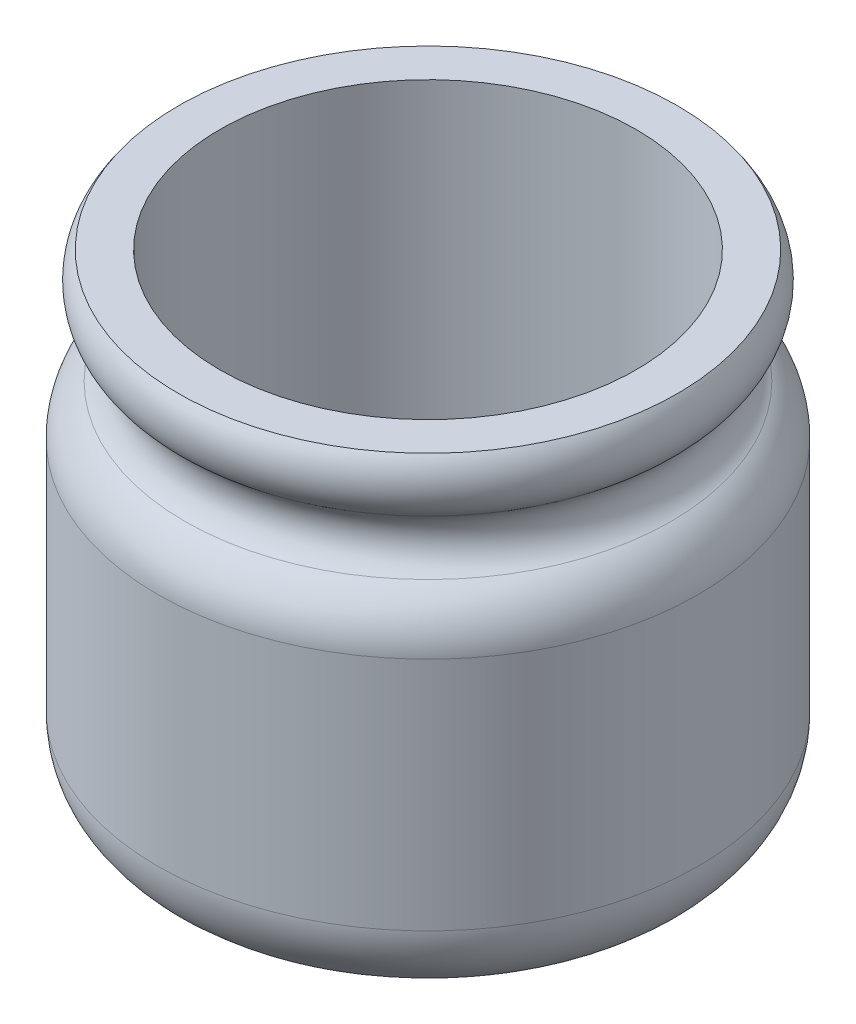
SolidWorks part; units mm, degrees
ref_plane "정면" through (0, 0, 0) normal (0, 0, 1) x (1, 0, 0)
ref_plane "윗면" through (0, 0, 0) normal (0, 1, 0) x (1, 0, 0)
ref_plane "우측면" through (0, 0, 0) normal (1, 0, 0) x (0, 0, -1)
sketch "스케치2" plane through (0, 0, 0) normal (1, 0, 0) x (0, 0, -1)
  line L0 (10.1, 0) -> (12.1, 0)
  line L1 (13.1, -7.9444) -> (13.1, -19.3593)
  line L2 (9.2593, -23.2) -> (0, -23.2)
  line L3 (0, -20.2) -> (0, 0) construction
  line L4 (10.1, 0) -> (10.1, -20.2)
  line L5 (10.1, -20.2) -> (0, -20.2)
  line L6 (0, -20.2) -> (0, -23.2)
  arc A0 (12.1, 0) -> (11.7965, -2.8572) centre (10.4532, -1.2698) cw
  arc A1 (11.7965, -2.8572) -> (11.7965, -5.5189) centre (12.6772, -4.1881) ccw
  arc A2 (11.7965, -5.5189) -> (13.1, -7.9444) centre (10.1915, -7.9444) cw
  arc A3 (13.1, -19.3593) -> (9.2593, -23.2) centre (9.2593, -19.3593) cw
  dimension "D3" = 20.2
  dimension "D4" = 2
  dimension "D1" = 10.1
  dimension "D2" = 3
  dimension "D5" = 3
  dimension "D8" = 20.2
revolve "회전1" add sketch "스케치2" angle 360 about L3
